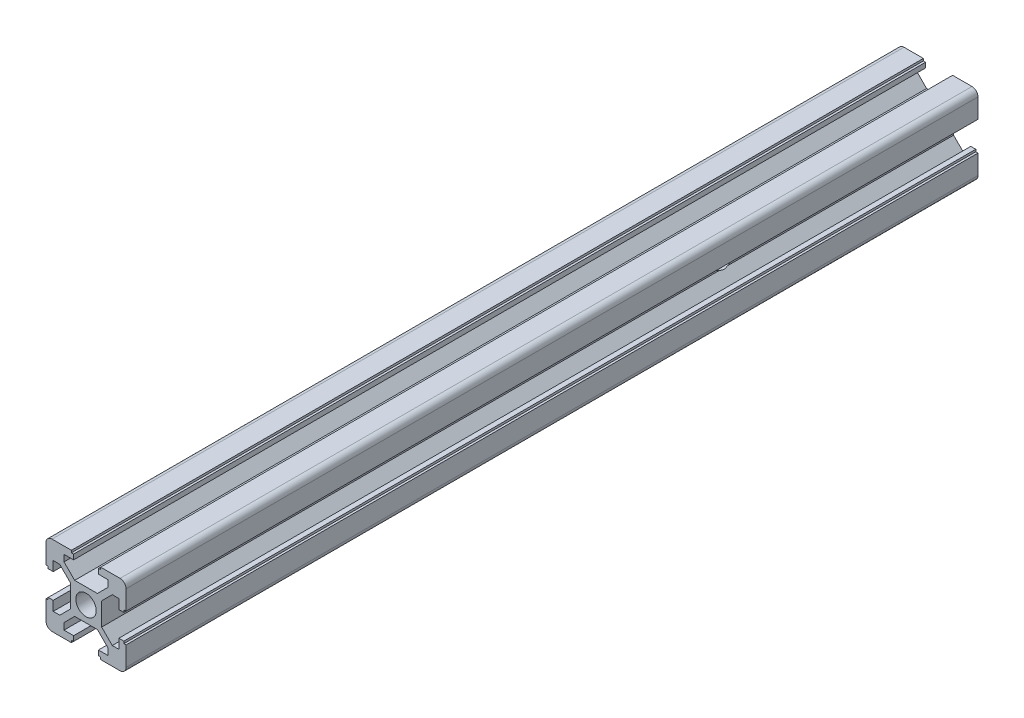
SolidWorks part; units mm, degrees
material "6063-T5"
ref_plane "前视基准面" through (0, 0, 0) normal (0, 0, 1) x (1, 0, 0)
ref_plane "上视基准面" through (0, 0, 0) normal (0, 1, 0) x (1, 0, 0)
ref_plane "右视基准面" through (0, 0, 0) normal (1, 0, 0) x (0, 0, -1)
sketch "草图2" plane through (0, 0, 0) normal (0, 0, 1) x (1, 0, 0)
  line L0 (-3.9, 2.8393) -> (-6.5607, 5.5)
  line L1 (-2.8393, 3.9) -> (2.8393, 3.9)
  line L2 (-3.9, 2.8393) -> (-3.9, -2.8393)
  line L3 (-2.8393, -3.9) -> (2.8393, -3.9)
  line L4 (3.9, 2.8393) -> (3.9, -2.8393)
  line L5 (-3.9, 3.9) -> (3.9, -3.9) construction
  line L6 (-3.9, -3.9) -> (3.9, 3.9) construction
  line L7 (-2.8393, 3.9) -> (-5.5, 6.5607)
  line L8 (-5.5, 6.5607) -> (-5.5, 8.2)
  line L9 (-5.5, 8.2) -> (-3.1, 8.2)
  line L10 (-3.1, 8.2) -> (-3.1, 9.45)
  line L11 (-3.1, 9.45) -> (-3.65, 9.45)
  line L12 (-3.65, 9.45) -> (-3.65, 10)
  line L13 (-3.65, 10) -> (-8.5, 10)
  line L14 (-6.5607, 5.5) -> (-8.2, 5.5)
  line L15 (-10, 3.65) -> (-10, 8.5)
  line L16 (-9.45, 3.65) -> (-10, 3.65)
  line L17 (-9.45, 3.1) -> (-9.45, 3.65)
  line L18 (-8.2, 3.1) -> (-9.45, 3.1)
  line L19 (-8.2, 5.5) -> (-8.2, 3.1)
  line L20 (2.8393, 3.9) -> (5.5, 6.5607)
  line L21 (3.9, 2.8393) -> (6.5607, 5.5)
  line L22 (6.5607, 5.5) -> (8.2, 5.5)
  line L23 (8.2, 5.5) -> (8.2, 3.1)
  line L24 (8.2, 3.1) -> (9.45, 3.1)
  line L25 (9.45, 3.1) -> (9.45, 3.65)
  line L26 (9.45, 3.65) -> (10, 3.65)
  line L27 (10, 3.65) -> (10, 8.5)
  line L28 (5.5, 6.5607) -> (5.5, 8.2)
  line L29 (3.65, 10) -> (8.5, 10)
  line L30 (3.65, 9.45) -> (3.65, 10)
  line L31 (3.1, 9.45) -> (3.65, 9.45)
  line L32 (3.1, 8.2) -> (3.1, 9.45)
  line L33 (5.5, 8.2) -> (3.1, 8.2)
  line L34 (3.9, -2.8393) -> (6.5607, -5.5)
  line L35 (2.8393, -3.9) -> (5.5, -6.5607)
  line L36 (5.5, -6.5607) -> (5.5, -8.2)
  line L37 (5.5, -8.2) -> (3.1, -8.2)
  line L38 (3.1, -8.2) -> (3.1, -9.45)
  line L39 (3.1, -9.45) -> (3.65, -9.45)
  line L40 (3.65, -9.45) -> (3.65, -10)
  line L41 (3.65, -10) -> (8.5, -10)
  line L42 (6.5607, -5.5) -> (8.2, -5.5)
  line L43 (10, -3.65) -> (10, -8.5)
  line L44 (9.45, -3.65) -> (10, -3.65)
  line L45 (9.45, -3.1) -> (9.45, -3.65)
  line L46 (8.2, -3.1) -> (9.45, -3.1)
  line L47 (8.2, -5.5) -> (8.2, -3.1)
  line L48 (-2.8393, -3.9) -> (-5.5, -6.5607)
  line L49 (-3.9, -2.8393) -> (-6.5607, -5.5)
  line L50 (-6.5607, -5.5) -> (-8.2, -5.5)
  line L51 (-8.2, -5.5) -> (-8.2, -3.1)
  line L52 (-8.2, -3.1) -> (-9.45, -3.1)
  line L53 (-9.45, -3.1) -> (-9.45, -3.65)
  line L54 (-9.45, -3.65) -> (-10, -3.65)
  line L55 (-10, -3.65) -> (-10, -8.5)
  line L56 (-5.5, -6.5607) -> (-5.5, -8.2)
  line L57 (-3.65, -10) -> (-8.5, -10)
  line L58 (-3.65, -9.45) -> (-3.65, -10)
  line L59 (-3.1, -9.45) -> (-3.65, -9.45)
  line L60 (-3.1, -8.2) -> (-3.1, -9.45)
  line L61 (-5.5, -8.2) -> (-3.1, -8.2)
  circle A0 centre (0, 0) radius 2.55
  arc A1 (-8.5, 10) -> (-10, 8.5) centre (-8.5, 8.5) ccw
  arc A2 (10, 8.5) -> (8.5, 10) centre (8.5, 8.5) ccw
  arc A3 (8.5, -10) -> (10, -8.5) centre (8.5, -8.5) ccw
  arc A4 (-10, -8.5) -> (-8.5, -10) centre (-8.5, -8.5) ccw
  point P25 (-10, 10)
  point P79 (0, 0)
  dimension "D1" = 5.1
  dimension "D9" = 1.5
  dimension "D2" = 7.8
  dimension "D3" = 1.5
  dimension "D4" = 10
  dimension "D5" = 3.1
  dimension "D6" = 0.55
  dimension "D7" = 1.8
  dimension "D8" = 5.5
  dimension "D11" = 3.9
  dimension "D10" = 4
extrude "凸台-拉伸1" add sketch "草图2" along normal blind 212.84
sketch "草图3" plane through (10, 0, 0) normal (1, 0, 0) x (0, 0, -1)
  circle A0 centre (-57.5, 0) radius 3
  circle A1 centre (-302.5, 0) radius 3
  dimension "D1" = 6
  dimension "D2" = 6
extrude "切除-拉伸1" cut sketch "草图3" against normal through all
